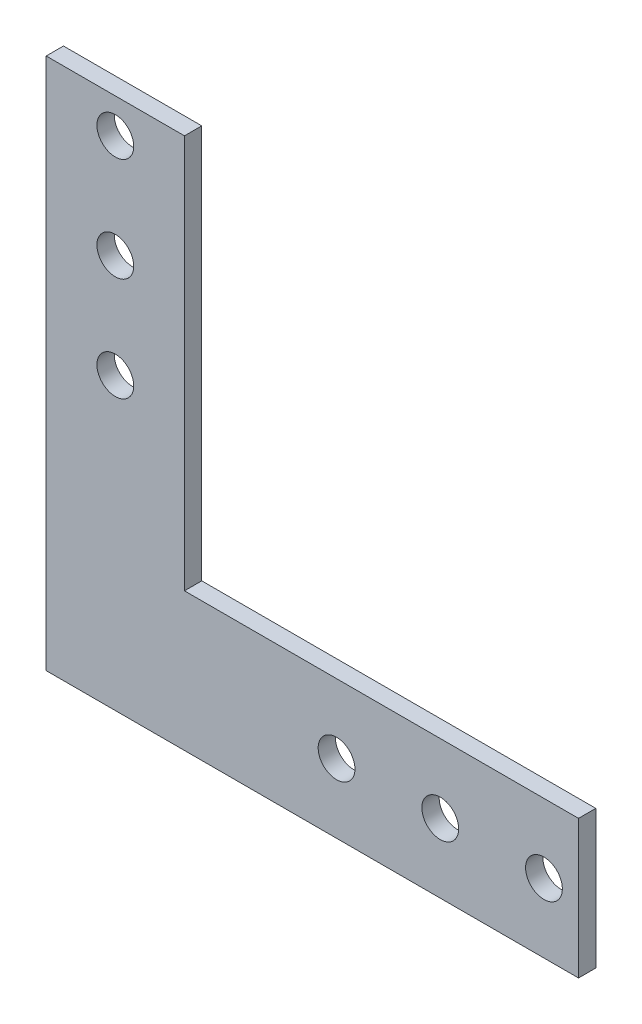
SolidWorks part; units mm, degrees
ref_plane "Front Plane" through (0, 0, 0) normal (0, 0, 1) x (1, 0, 0)
ref_plane "Top Plane" through (0, 0, 0) normal (0, 1, 0) x (1, 0, 0)
ref_plane "Right Plane" through (0, 0, 0) normal (1, 0, 0) x (0, 0, -1)
sketch "Sketch1" plane through (0, 0, 0) normal (0, 0, 1) x (1, 0, 0)
  line L1 (0, 0) -> (25.4, 0)
  line L2 (0, 0) -> (0, 97.79)
  line L3 (0, 97.79) -> (25.4, 97.79)
  line L4 (25.4, 25.4) -> (25.4, 79.8295)
  line L5 (0, 0) -> (97.79, 0)
  line L6 (0, 0) -> (0, 25.4)
  line L7 (25.4, 25.4) -> (79.8295, 25.4)
  line L8 (97.79, 0) -> (97.79, 25.4)
  line L11 (25.4, 97.79) -> (25.4, 79.8295)
  line L12 (79.8295, 25.4) -> (97.79, 25.4)
  dimension "D1" = 25.4
  dimension "D2" = 25.4
  dimension "D3" = 97.79
  dimension "D4" = 97.79
  dimension "D7" = 17.9605
extrude "Boss-Extrude1" add sketch "Sketch1" along normal blind 3.175 contours L5 L8 L7 L4 L3 L2 L1
sketch "Sketch2" plane through (0, 0, 3.175) normal (0, 0, 1) x (1, 0, 0)
  line L0 (0, 0) -> (97.79, 0) construction
  line L1 (0, 0) -> (0, 97.79) construction
  line L2 (25.4, 25.4) -> (97.79, 25.4) construction
  circle A0 centre (53.34, 12.7) radius 3.3782
  circle A1 centre (72.39, 12.7) radius 3.3782
  circle A2 centre (12.7, 53.34) radius 3.3782
  circle A3 centre (12.7, 72.39) radius 3.3782
  circle A4 centre (12.7, 91.44) radius 3.3782
  circle A5 centre (91.44, 12.7) radius 3.3782
  dimension "D5" = 6.7564
  dimension "D6" = 6.7564
  dimension "D7" = 6.7564
  dimension "D8" = 6.7564
  dimension "D9" = 6.7564
  dimension "D10" = 6.7564
  dimension "D1" = 53.34
  dimension "D2" = 53.34
  dimension "D3" = 19.05
  dimension "D4" = 19.05
  dimension "D11" = 19.05
  dimension "D12" = 19.05
  dimension "D13" = 12.7
  dimension "D14" = 12.7
  dimension "D15" = 12.7
  dimension "D16" = 12.7
  dimension "D17" = 12.7
  dimension "D18" = 12.7
extrude "Cut-Extrude1" cut sketch "Sketch2" against normal through all
